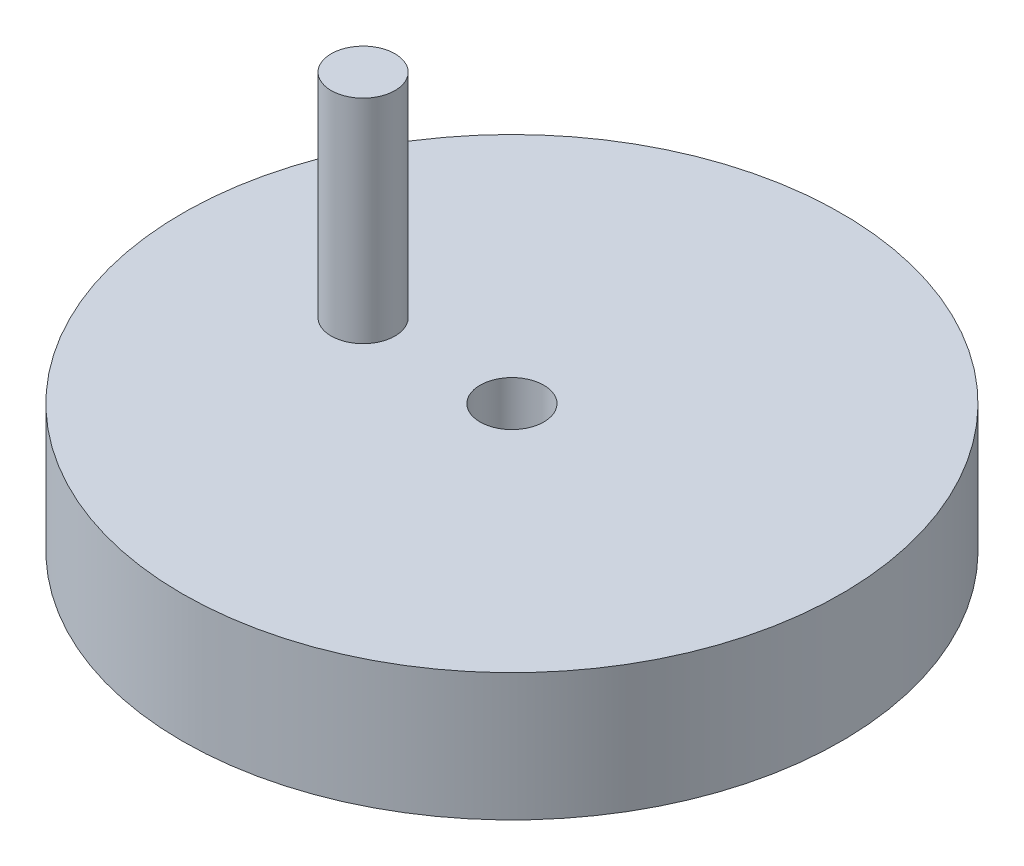
SolidWorks part; units mm, degrees
ref_plane "Front Plane" through (0, 0, 0) normal (0, 0, 1) x (1, 0, 0)
ref_plane "Top Plane" through (0, 0, 0) normal (0, 1, 0) x (1, 0, 0)
ref_plane "Right Plane" through (0, 0, 0) normal (1, 0, 0) x (0, 0, -1)
sketch "Sketch1" plane through (0, 0, 0) normal (0, 1, 0) x (1, 0, 0)
  circle A0 centre (0, 0) radius 31
  dimension "D1" = 62
extrude "Boss-Extrude1" add sketch "Sketch1" along normal blind 12
sketch "Sketch2" plane through (0, 12, 0) normal (0, 1, 0) x (1, 0, 0)
  circle A0 centre (0, 0) radius 3
  point P3 (0, 0)
  dimension "D1" = 6
extrude "Cut-Extrude1" cut sketch "Sketch2" against normal through all
sketch "Sketch3" plane through (0, 12, 0) normal (0, 1, 0) x (1, 0, 0)
  circle A0 centre (-14, 0) radius 3
  dimension "D1" = 6
  dimension "D2" = 14
extrude "Boss-Extrude2" add sketch "Sketch3" along normal blind 20
